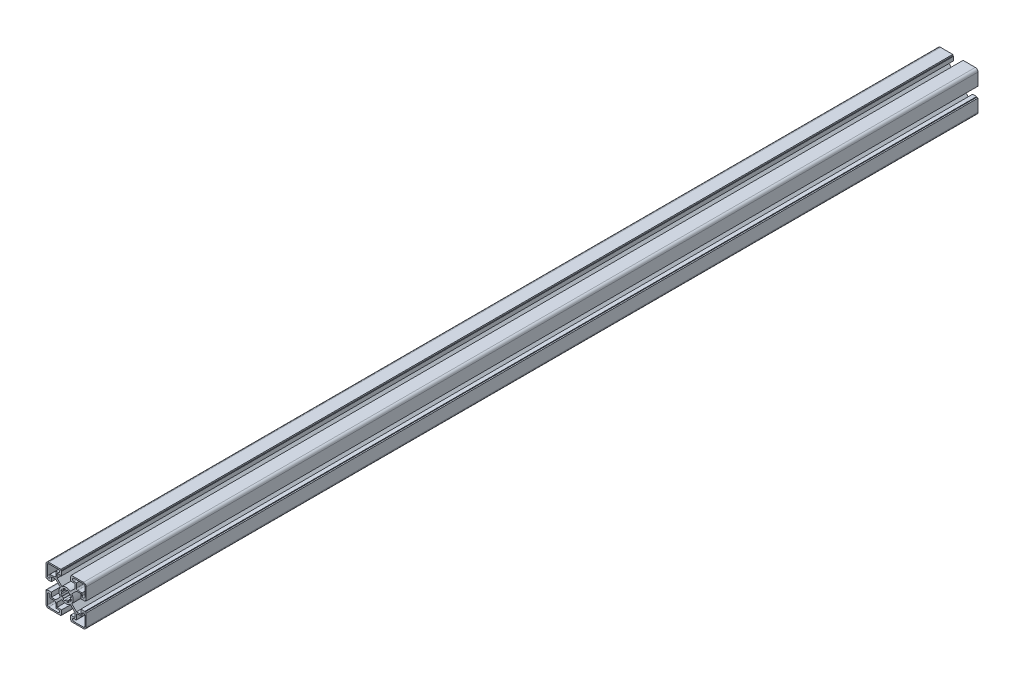
SolidWorks part; units mm, degrees
ref_plane "Front Plane" through (0, 0, 0) normal (0, 0, 1) x (1, 0, 0)
ref_plane "Top Plane" through (0, 0, 0) normal (0, 1, 0) x (1, 0, 0)
ref_plane "Right Plane" through (0, 0, 0) normal (1, 0, 0) x (0, 0, -1)
sketch "Sketch1" plane through (0, 0, 0) normal (0, 0, 1) x (1, 0, 0)
  line L2 (-19.5072, 22.5044) -> (-5.7912, 22.5044)
  line L3 (-5.7912, 22.5044) -> (-5.7912, 21.0058)
  line L4 (-5.7912, 21.0058) -> (-5.0038, 21.0058)
  line L6 (-5.0038, 21.0058) -> (-5.0038, 16.51)
  line L7 (-5.0038, 16.51) -> (-10.0457, 16.51)
  line L8 (-10.0457, 16.51) -> (-10.0457, 11.6801)
  line L9 (-10.0457, 11.6801) -> (-4.781, 6.4154)
  line L11 (-11.6801, 10.0457) -> (-6.4154, 4.781)
  line L12 (-16.51, 10.0457) -> (-11.6801, 10.0457)
  line L13 (-16.51, 5.0038) -> (-16.51, 10.0457)
  line L14 (-21.0058, 5.0038) -> (-16.51, 5.0038)
  line L15 (-21.0058, 5.7912) -> (-21.0058, 5.0038)
  line L16 (-22.5044, 5.7912) -> (-21.0058, 5.7912)
  line L17 (-22.5044, 19.5072) -> (-22.5044, 5.7912)
  line L18 (-18.0086, 11.5443) -> (-13.0429, 11.5443)
  line L19 (-18.0086, 11.5443) -> (-18.0086, 8.7884)
  line L20 (-11.5443, 18.0086) -> (-11.5443, 13.0429)
  line L21 (-21.0058, 19.5072) -> (-21.0058, 8.7884)
  line L23 (-11.5443, 18.0086) -> (-8.7884, 18.0086)
  line L24 (-19.5072, 21.0058) -> (-8.7884, 21.0058)
  line L25 (1.1893, 5.9789) -> (0.9762, 4.9077)
  line L26 (-1.1893, 5.9789) -> (-0.9762, 4.9077)
  line L27 (5.0686, 3.3868) -> (4.1605, 2.78)
  line L28 (3.3868, 5.0686) -> (2.78, 4.1605)
  line L29 (5.9789, -1.1893) -> (4.9077, -0.9762)
  line L30 (5.9789, 1.1893) -> (4.9077, 0.9762)
  line L31 (3.3868, -5.0686) -> (2.78, -4.1605)
  line L32 (5.0686, -3.3868) -> (4.1605, -2.78)
  line L33 (-1.1893, -5.9789) -> (-0.9762, -4.9077)
  line L34 (1.1893, -5.9789) -> (0.9762, -4.9077)
  line L35 (-5.0686, -3.3868) -> (-4.1605, -2.78)
  line L36 (-3.3868, -5.0686) -> (-2.78, -4.1605)
  line L37 (-5.9789, 1.1893) -> (-4.9077, 0.9762)
  line L38 (-5.9789, -1.1893) -> (-4.9077, -0.9762)
  line L39 (-3.3868, 5.0686) -> (-2.78, 4.1605)
  line L40 (-5.0686, 3.3868) -> (-4.1605, 2.78)
  line L41 (11.5443, 18.0086) -> (8.7884, 18.0086)
  line L42 (19.5072, 21.0058) -> (8.7884, 21.0058)
  line L43 (19.5072, 22.5044) -> (5.7912, 22.5044)
  line L44 (5.7912, 22.5044) -> (5.7912, 21.0058)
  line L45 (5.7912, 21.0058) -> (5.0038, 21.0058)
  line L46 (5.0038, 21.0058) -> (5.0038, 16.51)
  line L47 (5.0038, 16.51) -> (10.0457, 16.51)
  line L48 (10.0457, 16.51) -> (10.0457, 11.6801)
  line L49 (10.0457, 11.6801) -> (4.781, 6.4154)
  line L50 (11.6801, 10.0457) -> (6.4154, 4.781)
  line L51 (21.0058, 19.5072) -> (21.0058, 8.7884)
  line L52 (11.5443, 18.0086) -> (11.5443, 13.0429)
  line L53 (18.0086, 11.5443) -> (18.0086, 8.7884)
  line L54 (18.0086, 11.5443) -> (13.0429, 11.5443)
  line L55 (22.5044, 19.5072) -> (22.5044, 5.7912)
  line L56 (22.5044, 5.7912) -> (21.0058, 5.7912)
  line L57 (21.0058, 5.7912) -> (21.0058, 5.0038)
  line L58 (21.0058, 5.0038) -> (16.51, 5.0038)
  line L59 (16.51, 5.0038) -> (16.51, 10.0457)
  line L60 (16.51, 10.0457) -> (11.6801, 10.0457)
  line L61 (16.51, -10.0457) -> (11.6801, -10.0457)
  line L62 (16.51, -5.0038) -> (16.51, -10.0457)
  line L63 (21.0058, -5.0038) -> (16.51, -5.0038)
  line L64 (21.0058, -5.7912) -> (21.0058, -5.0038)
  line L65 (22.5044, -5.7912) -> (21.0058, -5.7912)
  line L66 (22.5044, -19.5072) -> (22.5044, -5.7912)
  line L67 (18.0086, -11.5443) -> (13.0429, -11.5443)
  line L68 (18.0086, -11.5443) -> (18.0086, -8.7884)
  line L69 (11.5443, -18.0086) -> (11.5443, -13.0429)
  line L70 (21.0058, -19.5072) -> (21.0058, -8.7884)
  line L71 (11.6801, -10.0457) -> (6.4154, -4.781)
  line L72 (10.0457, -11.6801) -> (4.781, -6.4154)
  line L73 (10.0457, -16.51) -> (10.0457, -11.6801)
  line L74 (5.0038, -16.51) -> (10.0457, -16.51)
  line L75 (5.0038, -21.0058) -> (5.0038, -16.51)
  line L76 (5.7912, -21.0058) -> (5.0038, -21.0058)
  line L77 (5.7912, -22.5044) -> (5.7912, -21.0058)
  line L78 (19.5072, -22.5044) -> (5.7912, -22.5044)
  line L79 (19.5072, -21.0058) -> (8.7884, -21.0058)
  line L80 (11.5443, -18.0086) -> (8.7884, -18.0086)
  line L81 (-11.5443, -18.0086) -> (-8.7884, -18.0086)
  line L82 (-19.5072, -21.0058) -> (-8.7884, -21.0058)
  line L83 (-19.5072, -22.5044) -> (-5.7912, -22.5044)
  line L84 (-5.7912, -22.5044) -> (-5.7912, -21.0058)
  line L85 (-5.7912, -21.0058) -> (-5.0038, -21.0058)
  line L86 (-5.0038, -21.0058) -> (-5.0038, -16.51)
  line L87 (-5.0038, -16.51) -> (-10.0457, -16.51)
  line L88 (-10.0457, -16.51) -> (-10.0457, -11.6801)
  line L89 (-10.0457, -11.6801) -> (-4.781, -6.4154)
  line L90 (-11.6801, -10.0457) -> (-6.4154, -4.781)
  line L91 (-21.0058, -19.5072) -> (-21.0058, -8.7884)
  line L92 (-11.5443, -18.0086) -> (-11.5443, -13.0429)
  line L93 (-18.0086, -11.5443) -> (-18.0086, -8.7884)
  line L94 (-18.0086, -11.5443) -> (-13.0429, -11.5443)
  line L95 (-22.5044, -19.5072) -> (-22.5044, -5.7912)
  line L96 (-22.5044, -5.7912) -> (-21.0058, -5.7912)
  line L97 (-21.0058, -5.7912) -> (-21.0058, -5.0038)
  line L98 (-21.0058, -5.0038) -> (-16.51, -5.0038)
  line L99 (-16.51, -5.0038) -> (-16.51, -10.0457)
  line L100 (-16.51, -10.0457) -> (-11.6801, -10.0457)
  arc A0 (-22.5044, 19.5072) -> (-19.5072, 22.5044) centre (-19.5072, 19.5072) cw
  arc A1 (-21.0058, 8.7884) -> (-18.0086, 8.7884) centre (-19.5072, 8.7884) ccw
  arc A2 (-21.0058, 19.5072) -> (-19.5072, 21.0058) centre (-19.5072, 19.5072) cw
  arc A3 (-8.7884, 21.0058) -> (-8.7884, 18.0086) centre (-8.7884, 19.5072) cw
  arc A4 (-11.5443, 13.0429) -> (-13.0429, 11.5443) centre (-13.0429, 13.0429) cw
  arc A5 (6.4154, -4.781) -> (6.4154, 4.781) centre (0, 0) ccw
  arc A6 (0.9762, 4.9077) -> (-0.9762, 4.9077) centre (0, 0) ccw
  arc A7 (-5.0686, 3.3868) -> (-5.9789, 1.1893) centre (0, 0) ccw
  arc A8 (4.1605, 2.78) -> (2.78, 4.1605) centre (0, 0) ccw
  arc A9 (4.9077, -0.9762) -> (4.9077, 0.9762) centre (0, 0) ccw
  arc A10 (2.78, -4.1605) -> (4.1605, -2.78) centre (0, 0) ccw
  arc A11 (-0.9762, -4.9077) -> (0.9762, -4.9077) centre (0, 0) ccw
  arc A12 (-4.1605, -2.78) -> (-2.78, -4.1605) centre (0, 0) ccw
  arc A13 (-4.9077, 0.9762) -> (-4.9077, -0.9762) centre (0, 0) ccw
  arc A14 (-2.78, 4.1605) -> (-4.1605, 2.78) centre (0, 0) ccw
  arc A15 (-5.9789, -1.1893) -> (-5.0686, -3.3868) centre (0, 0) ccw
  arc A16 (-3.3868, -5.0686) -> (-1.1893, -5.9789) centre (0, 0) ccw
  arc A17 (1.1893, -5.9789) -> (3.3868, -5.0686) centre (0, 0) ccw
  arc A18 (5.0686, -3.3868) -> (5.9789, -1.1893) centre (0, 0) ccw
  arc A19 (5.9789, 1.1893) -> (5.0686, 3.3868) centre (0, 0) ccw
  arc A20 (3.3868, 5.0686) -> (1.1893, 5.9789) centre (0, 0) ccw
  arc A21 (-1.1893, 5.9789) -> (-3.3868, 5.0686) centre (0, 0) ccw
  arc A22 (8.7884, 21.0058) -> (8.7884, 18.0086) centre (8.7884, 19.5072) ccw
  arc A23 (21.0058, 19.5072) -> (19.5072, 21.0058) centre (19.5072, 19.5072) ccw
  arc A24 (22.5044, 19.5072) -> (19.5072, 22.5044) centre (19.5072, 19.5072) ccw
  arc A25 (11.5443, 13.0429) -> (13.0429, 11.5443) centre (13.0429, 13.0429) ccw
  arc A26 (21.0058, 8.7884) -> (18.0086, 8.7884) centre (19.5072, 8.7884) cw
  arc A27 (21.0058, -8.7884) -> (18.0086, -8.7884) centre (19.5072, -8.7884) ccw
  arc A28 (11.5443, -13.0429) -> (13.0429, -11.5443) centre (13.0429, -13.0429) cw
  arc A29 (22.5044, -19.5072) -> (19.5072, -22.5044) centre (19.5072, -19.5072) cw
  arc A30 (21.0058, -19.5072) -> (19.5072, -21.0058) centre (19.5072, -19.5072) cw
  arc A31 (8.7884, -21.0058) -> (8.7884, -18.0086) centre (8.7884, -19.5072) cw
  arc A32 (-8.7884, -21.0058) -> (-8.7884, -18.0086) centre (-8.7884, -19.5072) ccw
  arc A33 (-21.0058, -19.5072) -> (-19.5072, -21.0058) centre (-19.5072, -19.5072) ccw
  arc A34 (-22.5044, -19.5072) -> (-19.5072, -22.5044) centre (-19.5072, -19.5072) ccw
  arc A35 (-11.5443, -13.0429) -> (-13.0429, -11.5443) centre (-13.0429, -13.0429) ccw
  arc A36 (-21.0058, -8.7884) -> (-18.0086, -8.7884) centre (-19.5072, -8.7884) cw
  arc A37 (4.781, 6.4154) -> (-4.781, 6.4154) centre (0, 0) ccw
  arc A38 (-4.781, -6.4154) -> (4.781, -6.4154) centre (0, 0) ccw
  arc A39 (-6.4154, 4.781) -> (-6.4154, -4.781) centre (0, 0) ccw
extrude "Boss-Extrude1" add sketch "Sketch1" along normal mid plane 1000
